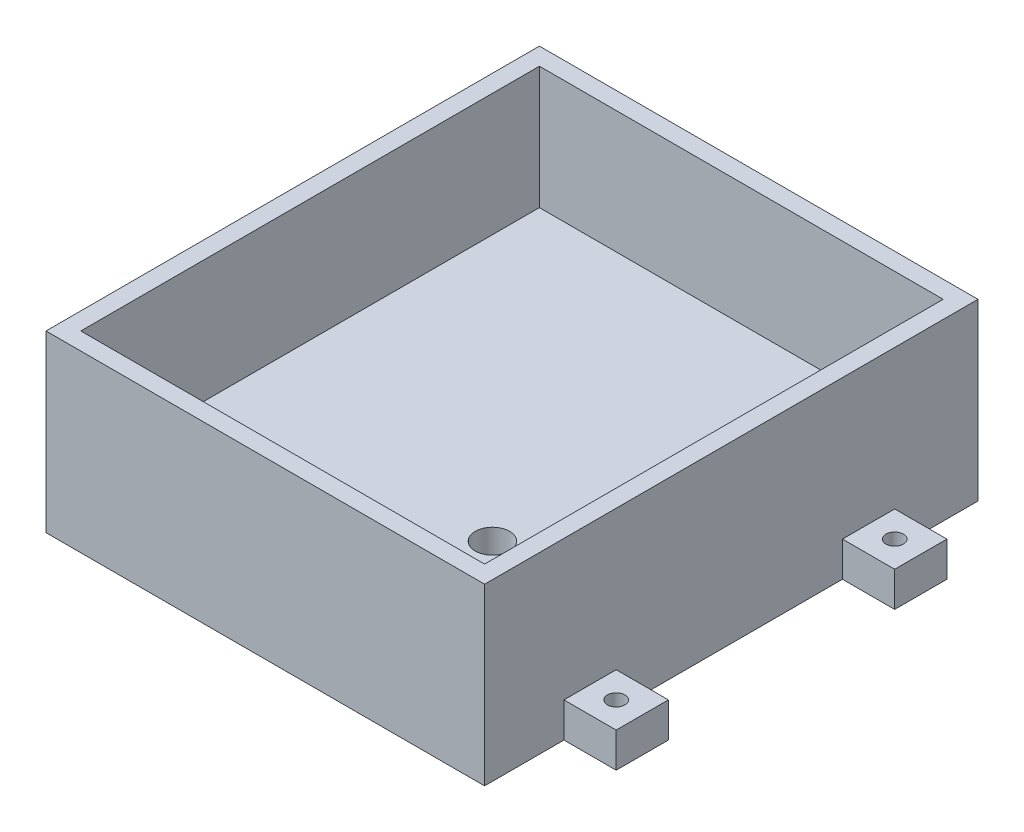
SolidWorks part; units mm, degrees
ref_plane "Front Plane" through (0, 0, 0) normal (0, 0, 1) x (1, 0, 0)
ref_plane "Top Plane" through (0, 0, 0) normal (0, 1, 0) x (1, 0, 0)
ref_plane "Right Plane" through (0, 0, 0) normal (1, 0, 0) x (0, 0, -1)
sketch "Sketch1" plane through (0, 0, 0) normal (0, 1, 0) x (1, 0, 0)
  line L1 (-80, -90) -> (80, -90)
  line L2 (-80, -90) -> (-80, 90)
  line L3 (-80, 90) -> (80, 90)
  line L4 (80, -90) -> (80, 90)
  line L5 (-80, -90) -> (80, 90) construction
  line L6 (-80, 90) -> (80, -90) construction
  point P0 (0, 0)
  dimension "D1" = 160
  dimension "D2" = 180
extrude "Boss-Extrude1" add sketch "Sketch1" along normal blind 19.05
sketch "Sketch2" plane through (0, 19.05, 0) normal (0, 1, 0) x (1, 0, 0)
  line L1 (-80, 90) -> (80, 90)
  line L2 (-80, 90) -> (-80, -90)
  line L3 (-80, -90) -> (80, -90)
  line L4 (80, 90) -> (80, -90)
  line L5 (-73.65, 83.65) -> (73.65, 83.65)
  line L6 (-73.65, 83.65) -> (-73.65, -83.65)
  line L7 (-73.65, -83.65) -> (73.65, -83.65)
  line L8 (73.65, 83.65) -> (73.65, -83.65)
  dimension "D1" = 6.35
  dimension "D2" = 6.35
  dimension "D3" = 6.35
  dimension "D4" = 6.35
extrude "Boss-Extrude2" add sketch "Sketch2" along normal blind 44.68
sketch "Sketch3" plane through (0, 19.05, 0) normal (0, 1, 0) x (1, 0, 0)
  circle A1 centre (38.41, -45.55) radius 6.254
  circle A2 centre (23.17, -45.55) radius 6.254
  circle A9 centre (38.41, -30.31) radius 6.254
  circle A10 centre (23.17, -30.31) radius 6.254
  dimension "D4" = 2
extrude "Cut-Extrude1" cut sketch "Sketch3" against normal blind 12.7
sketch "Sketch4" plane through (0, 0, 0) normal (0, -1, 0) x (1, 0, 0)
  line L1 (-80, -59.605) -> (-99.05, -59.605)
  line L2 (-80, -59.605) -> (-80, -40.555)
  line L3 (-80, -40.555) -> (-99.05, -40.555)
  line L4 (-99.05, -59.605) -> (-99.05, -40.555)
  line L5 (80, -90) -> (-80, -90) construction
  line L6 (-80, 41.995) -> (-99.05, 41.995)
  line L7 (-80, 41.995) -> (-80, 61.045)
  line L8 (-80, 61.045) -> (-99.05, 61.045)
  line L9 (-99.05, 41.995) -> (-99.05, 61.045)
  line L12 (99.05, -59.605) -> (80, -59.605)
  line L13 (99.05, -59.605) -> (99.05, -40.555)
  line L14 (99.05, -40.555) -> (80, -40.555)
  line L15 (80, -59.605) -> (80, -40.555)
  line L16 (99.05, 41.995) -> (80, 41.995)
  line L17 (99.05, 41.995) -> (99.05, 61.045)
  line L18 (99.05, 61.045) -> (80, 61.045)
  line L19 (80, 41.995) -> (80, 61.045)
  circle A0 centre (-89.525, -50.08) radius 3.175
  circle A1 centre (-89.525, 51.52) radius 3.175
  circle A2 centre (89.525, -50.08) radius 3.175
  circle A3 centre (89.525, 51.52) radius 3.175
  dimension "D5" = 9.525
  dimension "D7" = 9.525
  dimension "D1" = 19.05
  dimension "D2" = 19.05
  dimension "D3" = 19.05
  dimension "D4" = 19.05
  dimension "D6" = 9.525
  dimension "D8" = 9.525
  dimension "D9" = 101.6
  dimension "D10" = 39.92
  dimension "D11" = 2
extrude "Boss-Extrude3" add sketch "Sketch4" against normal blind 12.7
